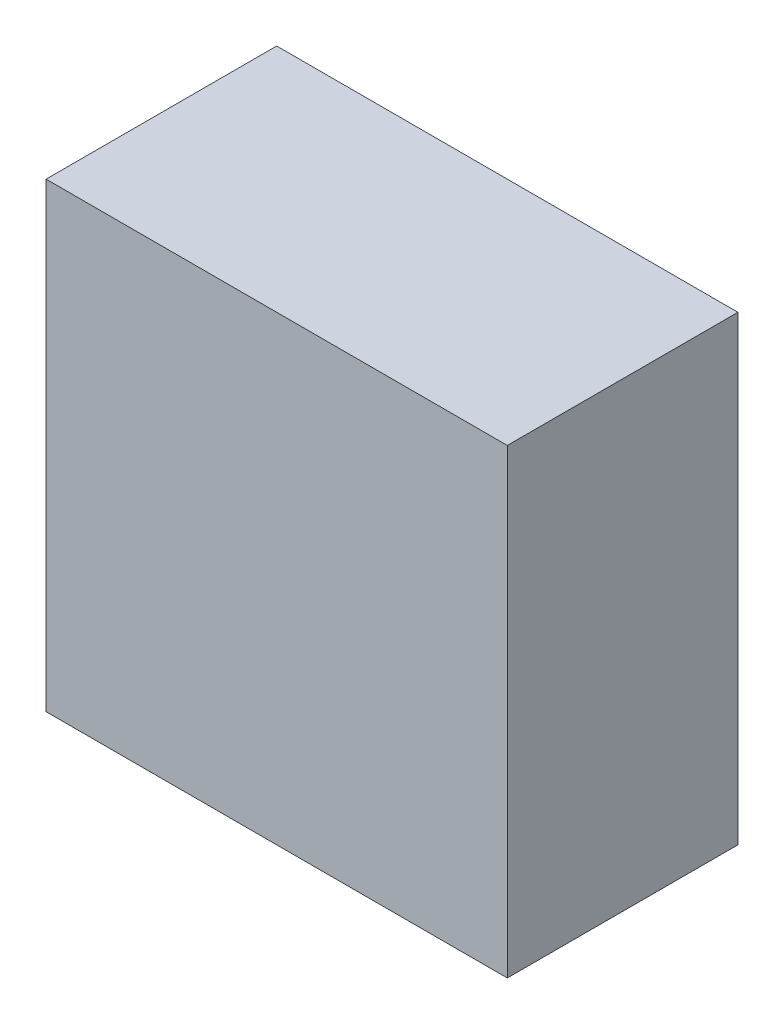
SolidWorks part; units mm, degrees
ref_plane "Front Plane" through (0, 0, 0) normal (0, 0, 1) x (1, 0, 0)
ref_plane "Top Plane" through (0, 0, 0) normal (0, 1, 0) x (1, 0, 0)
ref_plane "Right Plane" through (0, 0, 0) normal (1, 0, 0) x (0, 0, -1)
sketch "Sketch1" plane through (0, 0, 0) normal (0, 0, 1) x (1, 0, 0)
  line L1 (0, 0) -> (3048, 0)
  line L2 (0, 0) -> (0, 3048)
  line L3 (0, 3048) -> (3048, 3048)
  line L4 (3048, 0) -> (3048, 3048)
  dimension "D1" = 3048
  dimension "D2" = 3048
extrude "Boss-Extrude1" add sketch "Sketch1" along normal blind 1524
